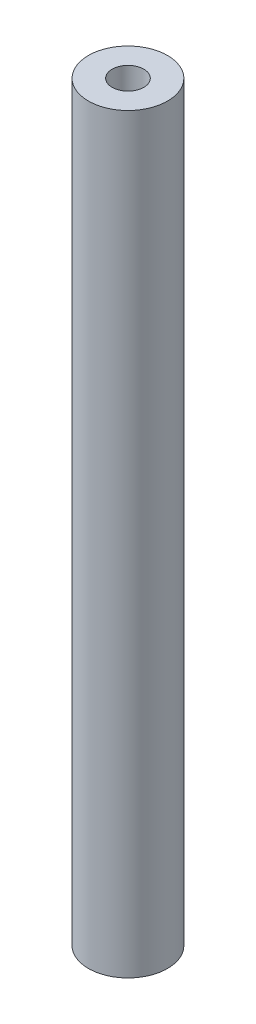
SolidWorks part; units mm, degrees
material "6061-T4 (SS)"
ref_plane "Front Plane" through (0, 0, 0) normal (0, 0, 1) x (1, 0, 0)
ref_plane "Top Plane" through (0, 0, 0) normal (0, 1, 0) x (1, 0, 0)
ref_plane "Right Plane" through (0, 0, 0) normal (1, 0, 0) x (0, 0, -1)
sketch "Sketch1" plane through (0, 0, 0) normal (0, 1, 0) x (1, 0, 0)
  circle A0 centre (0, 0) radius 5
  dimension "D1" = 10
extrude "Boss-Extrude1" add sketch "Sketch1" along normal blind 103
hole_wizard "Ø4.0mm Dowel Hole1" positions "3DSketch1" profile "Sketch4" hole size "Ø4.0" standard "ANSI Metric"
sketch3d "3DSketch1"
  line L0 (0, 103, 0) -> (0, 0, 0) construction
  point P0 (0, 103, 0)
  point P5 (0, 0, 0)
sketch "Sketch4" plane through (0, 103, 0) normal (1, 0, 0) x (0, 0, 1)
  line L0 (0, 0) -> (0, 19.2017)
  line L1 (0, 19.2017) -> (2, 18)
  line L2 (2, 18) -> (2, 0.025)
  line L3 (2, 0.025) -> (2.025, 0)
  line L5 (2.025, 0) -> (0, 0)
  line L6 (-2, 0.025) -> (-2.025, 0) construction
  line L10 (0, 19.2017) -> (-2, 18) construction
  line L11 (0, -6.35) -> (0, 107.95) construction
  dimension "Hole Dia." = 4
  dimension "Hole Depth" = 18
  dimension "Near C'Sink Dia." = 4.05
  dimension "Near C'Sink Angle" = 90
  dimension "Drill Angle" = 118
cosmetic thread "Cosmetic Thread1"
ref_plane "Plane3" through (0, 51.5, 0) normal (0, 1, 0) x (1, 0, 0)
mirror "Mirror1" about plane through (0, 51.5, 0) normal (0, 1, 0) of "Ø4.0mm Dowel Hole1"
cosmetic thread "Cosmetic Thread2" parameters "D1"=15, "D2"=5
sketch "Sketch5" plane through (0, 0, 0) normal (0, 0, 1) x (1, 0, 0)
  line L0 (0, 51.5) -> (-5, 51.5) construction
  line L1 (-5, 103) -> (-4, 103)
  line L2 (-5, 103) -> (-5, 99)
  line L3 (-5, 99) -> (-4, 99)
  line L4 (-4, 103) -> (-4, 99)
  line L9 (5.5, 51.5) -> (-5.5, 51.5) construction
  line L10 (-5, 103) -> (-5, 0) construction
  line L11 (-4, 0) -> (-4, 4)
  line L12 (-5, 4) -> (-4, 4)
  line L13 (-5, 0) -> (-5, 4)
  line L14 (-5, 0) -> (-4, 0)
  line L15 (0, 103) -> (0, 0) construction
  line L16 (5, 103) -> (-5, 103) construction
  dimension "D1" = 4
  dimension "D2" = 4
revolve "Cut-Revolve2" cut sketch "Sketch5" angle 360 about L15
sketch "Sketch6" plane through (0, 99, 0) normal (0, 1, 0) x (1, 0, 0)
  circle A0 centre (0, 0) radius 5 construction
  circle A1 centre (0, 0) radius 5
extrude "Cut-Extrude1" cut sketch "Sketch6" along normal blind 20
mirror "Mirror3" about plane through (0, 51.5, 0) normal (0, 1, 0) of "Cut-Extrude1"
equation "\"D1@Boss-Extrude1\"=103"
